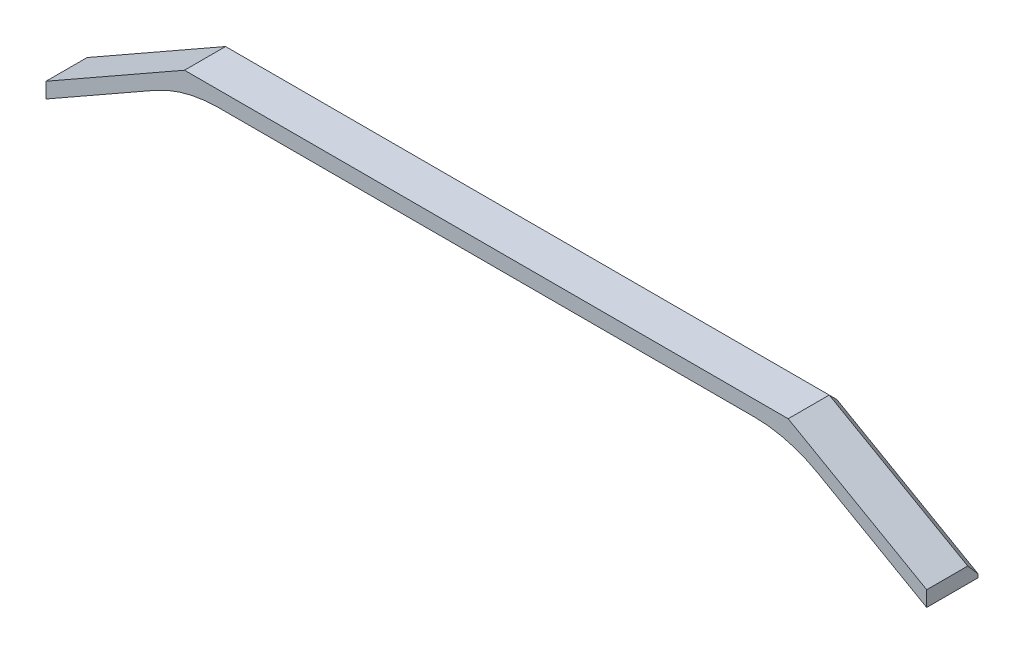
SolidWorks part; units mm, degrees
ref_plane "Front Plane" through (0, 0, 0) normal (0, 0, 1) x (1, 0, 0)
ref_plane "Top Plane" through (0, 0, 0) normal (0, 1, 0) x (1, 0, 0)
ref_plane "Right Plane" through (0, 0, 0) normal (1, 0, 0) x (0, 0, -1)
sketch "Sketch1" plane through (0, 0, 0) normal (0, 1, 0) x (1, 0, 0)
  line L0 (94.5092, 0) -> (-87.498, 0) construction
  line L2 (-96.7218, 5) -> (116.3146, 5) construction
  line L3 (0, -18.9109) -> (0, 34.8651) construction
  line L4 (85.3861, -68.1327) -> (-87.498, -68.1327) construction
  line L5 (-87.498, 0) -> (-87.498, -68.1327) construction
  line L6 (58.8301, 0) -> (-58.8301, 0)
  line L9 (-58.8301, 0) -> (-58.8301, 10)
  line L10 (58.8301, 0) -> (58.8301, 10)
  line L12 (-58.8301, 10) -> (58.8301, 10)
  point P3 (0, 0)
  dimension "D10" = 10
  dimension "D11" = 5
extrude "Boss-Extrude1" add sketch "Sketch1" along normal blind 3
chamfer "Chamfer1" distance 2 angle 45 1 edges at (0, 3, -10)
sketch "Sketch2" plane through (0, 3, 0) normal (0, 1, 0) x (1, 0, 0)
  line L0 (-96.4501, 5) -> (97.1945, 5) construction
  line L2 (-58.8301, 0) -> (58.8301, 0) construction
  line L3 (0, -12.1265) -> (0, 27.7783) construction
  circle A0 centre (-29, 5) radius 1.5
  circle A1 centre (29, 5) radius 1.5
  dimension "D2" = 3
  dimension "D3" = 3
  dimension "D1" = 5
  dimension "D4" = 29
  dimension "D5" = 29
extrude "Boss-Extrude2" add sketch "Sketch2" against normal blind 2 from surface at -3 starting at face at (0, 0, -5)
chamfer "Chamfer2" distance 0.3 angle 45 2 edges at (-29, -2, -6.5) (29, -2, -6.5)
sketch "Sketch3" plane through (0, 0, 0) normal (0, 0, 1) x (1, 0, 0)
  line L0 (-58.8301, 0) -> (-85.8301, -15.3616)
  line L1 (-85.8301, -15.3616) -> (-85.8301, -12.3616)
  line L2 (-85.8301, -12.3616) -> (-58.8301, 3)
  line L3 (-58.8301, 3) -> (-58.8301, 0)
  line L4 (0, 16.5715) -> (0, -29.0199) construction
  line L5 (58.8301, 3) -> (58.8301, 0)
  line L6 (85.8301, -12.3616) -> (58.8301, 3)
  line L7 (85.8301, -15.3616) -> (85.8301, -12.3616)
  line L8 (58.8301, 0) -> (85.8301, -15.3616)
  line L9 (-96.17, -22.5133) -> (-59.17, -1.4623) construction
  dimension "D1" = 27
extrude "Boss-Extrude3" add sketch "Sketch3" against normal blind 10
chamfer "Chamfer3" distance 2 angle 45 2 edges at (72.3301, -4.6808, -10) (-72.3301, -4.6808, -10)
fillet "Fillet1" radius 25 2 edges at (-58.8301, 0, -5) (58.8301, 0, -5)
